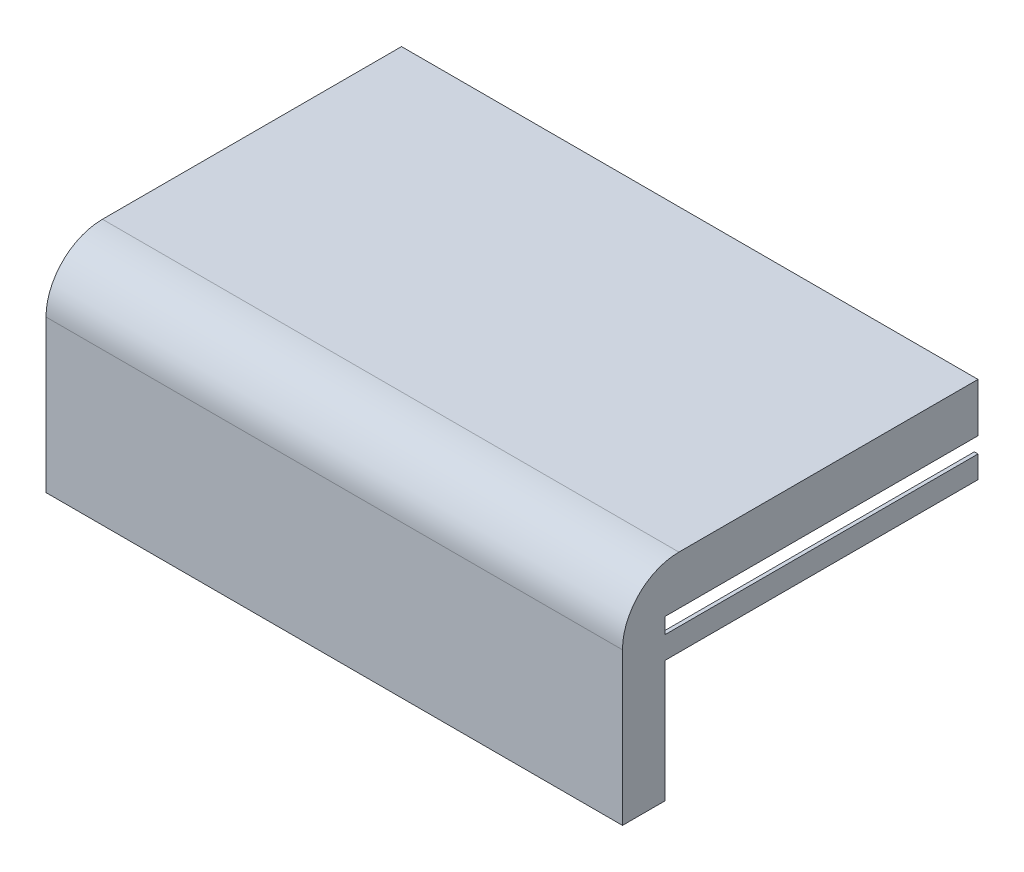
SolidWorks part; units mm, degrees
ref_plane "Front Plane" through (0, 0, 0) normal (0, 0, 1) x (1, 0, 0)
ref_plane "Top Plane" through (0, 0, 0) normal (0, 1, 0) x (1, 0, 0)
ref_plane "Right Plane" through (0, 0, 0) normal (1, 0, 0) x (0, 0, -1)
sketch "Sketch2" plane through (0, 0, 0) normal (0, 0, 1) x (1, 0, 0)
  line L0 (-62.1117, 22.8832) -> (-62.1117, -51.0168)
  line L1 (-62.1117, -51.0168) -> (142.1883, -51.0168)
  line L2 (142.1883, -51.0168) -> (142.1883, 22.8832)
  line L3 (142.1883, 22.8832) -> (-62.1117, 22.8832)
  dimension "D1" = 73.9
  dimension "D2" = 204.3
extrude "Boss-Extrude1" add sketch "Sketch2" along normal blind 126
sketch "Sketch3" plane through (142.1883, 0, 0) normal (1, 0, 0) x (0, 0, -1)
  line L0 (-126, -51.0168) -> (-126, 22.8832) construction
  line L1 (0, -51.0168) -> (-111, -51.0168)
  line L2 (0, -51.0168) -> (0, 5.5832)
  line L3 (0, 5.5832) -> (-111, 5.5832)
  line L4 (-111, -51.0168) -> (-111, 5.5832)
  line L5 (-126, 22.8832) -> (0, 22.8832) construction
  dimension "D1" = 15
  dimension "D2" = 17.3
extrude "Cut-Extrude2" cut sketch "Sketch3" against normal blind 274.3
fillet "Fillet1" radius 20 1 edges at (40.0383, 22.8832, 126)
sketch "Sketch5" plane through (142.1883, 0, 0) normal (1, 0, 0) x (0, 0, -1)
  line L0 (-111, 5.5832) -> (-111, -51.0168) construction
  line L1 (-111, -13.5168) -> (0, -13.5168)
  line L2 (-111, -13.5168) -> (-111, 5.5832)
  line L3 (-111, 5.5832) -> (0, 5.5832)
  line L4 (0, -13.5168) -> (0, 5.5832)
  line L6 (-111, 5.5832) -> (0, 5.5832)
  line L7 (-111, 5.5832) -> (-111, 0)
  line L8 (-111, 0) -> (0, 0)
  line L9 (0, 5.5832) -> (0, 0)
  line L10 (0, -13.5168) -> (-111, -13.5168)
  line L11 (0, -13.5168) -> (0, -7.9078)
  line L12 (0, -7.9078) -> (-111, -7.9078)
  line L13 (-111, -13.5168) -> (-111, -7.9078)
  dimension "D1" = 19.1
extrude "Boss-Extrude4" add sketch "Sketch5" against normal blind 1.3 contours L12 L4 L8 L2
